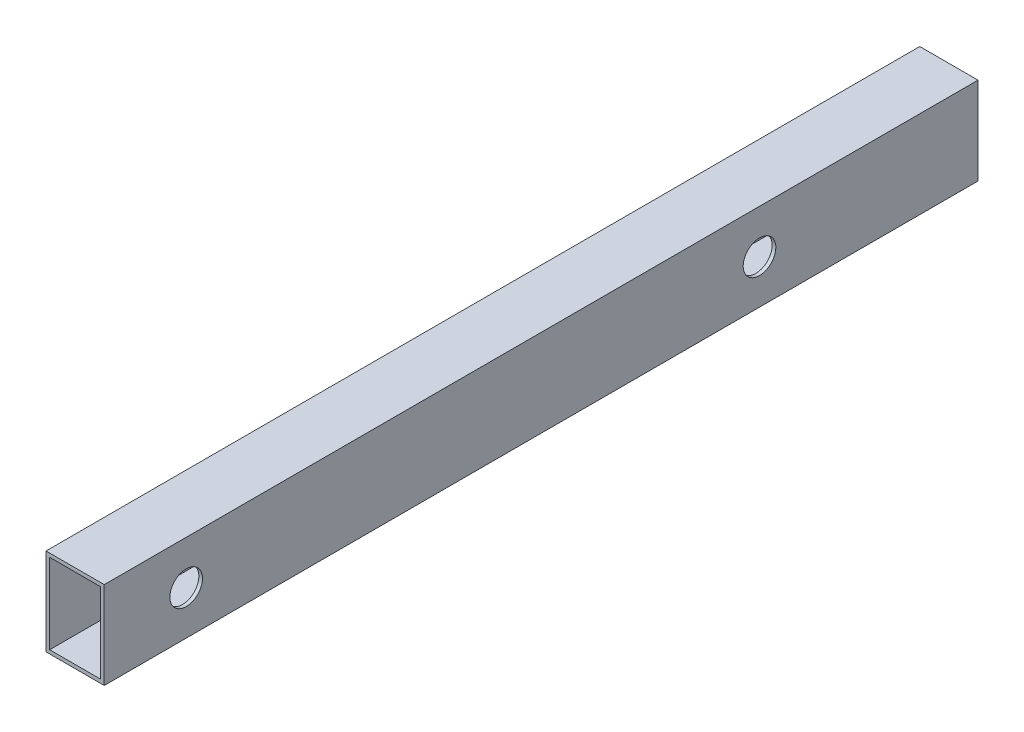
SolidWorks part; units mm, degrees
ref_plane "Front Plane" through (0, 0, 0) normal (0, 0, 1) x (1, 0, 0)
ref_plane "Top Plane" through (0, 0, 0) normal (0, 1, 0) x (1, 0, 0)
ref_plane "Right Plane" through (0, 0, 0) normal (1, 0, 0) x (0, 0, -1)
sketch "Sketch1" plane through (0, 0, 0) normal (0, 0, 1) x (1, 0, 0)
  line L0 (0, 38.1) -> (0, 34.925) construction
  line L1 (-25.4, 38.1) -> (25.4, 38.1)
  line L2 (-25.4, 38.1) -> (-25.4, -38.1)
  line L3 (-25.4, -38.1) -> (25.4, -38.1)
  line L4 (25.4, 38.1) -> (25.4, -38.1)
  line L5 (-25.4, 38.1) -> (25.4, -38.1) construction
  line L6 (-25.4, -38.1) -> (25.4, 38.1) construction
  line L7 (-22.225, 34.925) -> (22.225, 34.925)
  line L8 (-22.225, 34.925) -> (-22.225, -34.925)
  line L9 (-22.225, -34.925) -> (22.225, -34.925)
  line L10 (22.225, 34.925) -> (22.225, -34.925)
  line L11 (22.225, 0) -> (25.4, 0) construction
  line L12 (-22.225, 0) -> (-25.4, 0) construction
  line L13 (0, -34.925) -> (0, -38.1) construction
  point P0 (0, 0)
  dimension "D1" = 76.2
  dimension "D2" = 50.8
  dimension "D3" = 3.175
extrude "Boss-Extrude1" add sketch "Sketch1" along normal blind 762
sketch "Sketch2" plane through (0, 38.1, 0) normal (0, 1, 0) x (1, 0, 0)
  line L0 (-26.9875, -190.549) -> (26.9875, -190.549) construction
  line L1 (-25.4, 0) -> (25.4, 0)
  line L2 (-25.4, 0) -> (-25.4, -762)
  line L3 (-25.4, -762) -> (25.4, -762)
  line L4 (25.4, 0) -> (25.4, -762)
  line L5 (-26.4963, -703.2466) -> (26.4963, -703.2466) construction
  line L6 (0, -703.2466) -> (0, -190.549) construction
  line L7 (0, 0) -> (0, -190.549) construction
  line L8 (-74.6125, -402.6047) -> (-73.6301, -528.6965) construction
  line L9 (-74.1213, -465.6506) -> (-23.8125, -465.6506) construction
  line L10 (-23.8125, -465.6506) -> (26.9875, -465.6506) construction
  dimension "D1" = 190.549
  dimension "D2" = 512.6976
  dimension "D3" = 126.0917
  dimension "D4" = 50.3088
  dimension "D5" = 50.8
  dimension "D6" = 53.975
  dimension "D7" = 52.9926
  dimension "D8" = 275.1016
ref_plane "Plane1" through (25.4, 0, 0) normal (1, 0, 0) x (0, 0, -1)
sketch "Sketch4" plane through (25.4, 0, 0) normal (1, 0, 0) x (0, 0, -1)
  line L0 (-690.548, 38.1) -> (-690.548, 0) construction
  line L1 (-703.2466, 38.1) -> (-190.549, 38.1) construction
  line L2 (-190.549, 38.1) -> (-190.549, 0) construction
  line L3 (0, 38.1) -> (-190.549, 38.1) construction
  line L4 (-190.549, 0) -> (0, 0) construction
  line L5 (0, -38.1) -> (0, 38.1) construction
  line L6 (-190.549, 0) -> (-690.548, 0) construction
  circle A0 centre (-690.548, 0) radius 14.224
  circle A1 centre (-190.549, 0) radius 14.224
  dimension "D1" = 28.448
  dimension "D2" = 499.999
  dimension "D3" = 190.549
extrude "Cut-Extrude1" cut sketch "Sketch4" against normal up to surface (50.8 mm away) contours A1 | A0 up to face at (-25.4, 0, 381)
